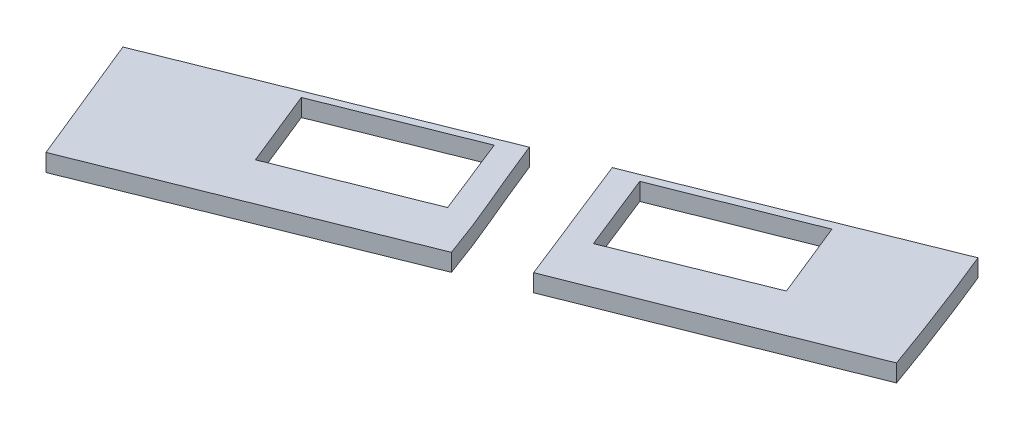
SolidWorks part; units mm, degrees
ref_plane "Front Plane" through (0, 0, 0) normal (0, 0, 1) x (1, 0, 0)
ref_plane "Top Plane" through (0, 0, 0) normal (0, 1, 0) x (1, 0, 0)
ref_plane "Right Plane" through (0, 0, 0) normal (1, 0, 0) x (0, 0, -1)
sketch "Sketch1" plane through (0, 0, 0) normal (0, 1, 0) x (1, 0, 0)
  line L0 (6.1521, 12.0078) -> (30.7603, 12.0078) construction
  line L1 (-3.9482, 25.8578) -> (34.7084, 30.3726)
  line L2 (41.3065, 14.4944) -> (26.3793, 8.5562)
  line L3 (26.3793, 8.5562) -> (21.5711, 20.6728)
  line L4 (22.9999, 7.2071) -> (6.3717, 0.5247)
  line L5 (6.3717, 0.5247) -> (-3.9482, 25.8578)
  line L6 (29.528, 24.668) -> (31.2954, 20.2924)
  line L11 (31.2954, 20.2924) -> (24.3349, 17.4974)
  line L12 (24.3349, 17.4974) -> (22.5827, 21.866)
  line L13 (22.5827, 21.866) -> (29.528, 24.668)
  line L14 (16.5778, 19.4932) -> (18.3623, 15.098)
  line L19 (18.3623, 15.098) -> (11.3765, 12.3133)
  line L20 (11.3765, 12.3133) -> (9.6115, 16.6866)
  line L21 (9.6115, 16.6866) -> (16.5778, 19.4932)
  line L22 (32.7866, 19.2988) -> (34.5598, 14.9094)
  line L23 (34.5598, 14.9094) -> (26.6479, 11.7224)
  line L24 (26.6479, 11.7224) -> (24.8826, 16.1536)
  line L25 (24.8826, 16.1536) -> (32.7866, 19.2988)
  line L26 (18.8984, 13.7726) -> (20.6613, 9.3244)
  line L27 (20.6613, 9.3244) -> (12.7599, 6.178)
  line L28 (12.7599, 6.178) -> (10.9743, 10.6019)
  line L29 (10.9743, 10.6019) -> (18.8984, 13.7726)
  circle A0 centre (31.582, 27.844) radius 1.2816
  circle A1 centre (4.4439, 18.6222) radius 1.2791
  spline S0 degree 3 poles (34.7084, 30.3726) (34.9423, 29.8626) (35.2165, 29.3692) (35.41, 28.8426) (35.6349, 28.2308) (35.7689, 27.5892) (35.9606, 26.9662) (35.9659, 26.9489) (35.9911, 26.9442) (35.9993, 26.9281) (36.7439, 25.465) (37.5642, 24.0369) (38.2178, 22.5309) (38.8653, 21.0391) (40.4414, 16.9604) (41.3065, 14.4944) knots 0 0 0 0 1 1 1 2 2 2 3 3 3 4 4 4 5 5 5 5
  spline S1 degree 3 poles (21.5711, 20.6728) (21.6349, 21.0182) (21.7486, 21.358) (21.7624, 21.7089) (21.7742, 22.0053) (21.6958, 22.2987) (21.6469, 22.5913) (21.6439, 22.6091) (21.6175, 22.614) (21.6085, 22.6296) (21.4549, 22.8982) (21.3835, 23.2349) (21.1477, 23.4352) (20.9055, 23.6408) (20.6926, 23.8883) (20.4183, 24.0487) (20.1599, 24.1998) (19.8708, 24.3154) (19.5741, 24.3552) (19.1803, 24.408) (18.7433, 24.4488) (18.3847, 24.2778) (18.1315, 24.1571) (17.8707, 24.0528) (17.6175, 23.9321) (17.6011, 23.9243) (17.5915, 23.9069) (17.5791, 23.8937) (17.3615, 23.6637) (17.1044, 23.4652) (16.9272, 23.2028) (16.7797, 22.9842) (16.6873, 22.7287) (16.6206, 22.4736) (16.5456, 22.1866) (16.5442, 21.8852) (16.506, 21.591) knots 0 0 0 0 1 1 1 2 2 2 3 3 3 4 4 4 5 5 5 6 6 6 7 7 7 8 8 8 9 9 9 10 10 10 11 11 11 12 12 12 12
  spline S2 degree 3 poles (16.506, 21.591) (16.5188, 21.5783) (16.5398, 21.5702) (16.5444, 21.5527) (16.6174, 21.2736) (16.6638, 20.9879) (16.7368, 20.7087) (16.8068, 20.441) (17.044, 20.2485) (17.1977, 20.0184) (17.4656, 19.6171) (18.0312, 19.5778) (18.2342, 19.0982) (19.1275, 16.9888) (19.3467, 16.3313) (20.0022, 14.687) (21.5189, 10.8821) (22.0115, 9.9866) (22.9999, 7.2071) knots 0 0 0 0 1 1 1 2 2 2 3 3 3 4 4 4 5 5 5 6 6 6 6
  dimension "D1" = 17.9207
extrude "Boss-Extrude1" add sketch "Sketch1" along normal blind 1.19
sketch "Sketch2" plane through (0, 0, 0) normal (0, -1, 0) x (1, 0, 0)
  line L0 (11.3765, -12.3133) -> (18.3623, -15.098) construction
  line L3 (0.5872, -6.8843) -> (39.4908, -22.5055)
  line L9 (-7.6928, -25.9504) -> (39.4908, -43.0645)
  line L10 (39.4908, -43.0645) -> (39.4908, -22.5055)
  line L11 (-7.6928, -25.9504) -> (0.5872, -6.8843)
  point P0 (31.6705, -19.3654)
  point P1 (24.7142, -16.5722)
  point P2 (18.6519, -14.1369)
  point P3 (11.6841, -11.3594)
  point P4 (39.4908, -43.0645)
  point P9 (-7.6928, -25.9504)
  dimension "D1" = 1
  dimension "D2" = 1
  dimension "D3" = 1
  dimension "D4" = 1
extrude "Cut-Extrude1" cut sketch "Sketch2" against normal blind 2.54
sketch "Sketch4" plane through (-2.2989, 0, -5.7254) normal (-0.3726, 0, -0.928) x (-0.928, 0, 0.3726)
  line L0 (-6.068, 1.19) -> (-6.068, 0) construction
  line L2 (-27.7006, 1.19) -> (-27.7006, 0) construction
  line L5 (-43.8706, 0) -> (-43.8706, 1.19) construction
  line L6 (-43.8706, 1.19) -> (-27.7006, 1.19) construction
  line L10 (-24.0343, 1.19) -> (-6.068, 1.19) construction
  line L11 (-24.0343, 0) -> (-24.0343, 1.19) construction
  line L12 (-6.068, 0.19) -> (-45.5948, 0.19)
  line L13 (-45.5948, 0.19) -> (-45.5948, -0.6194)
  line L14 (-45.5948, -0.6194) -> (-5.5595, -0.6194)
  line L15 (-5.5595, -0.6194) -> (-6.068, 0.19)
  point P0 (-24.0343, 0.19)
  point P4 (-27.7006, 0.19)
  point P5 (-6.068, 0.19)
  point P7 (-43.8706, 0.19)
  dimension "D1" = 1
  dimension "D2" = 1
  dimension "D3" = 1
  dimension "D4" = 1
extrude "Cut-Extrude2" cut sketch "Sketch4" against normal blind 9.906
